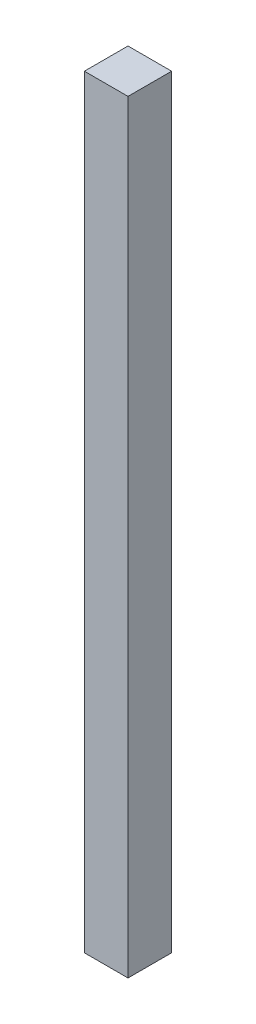
SolidWorks part; units mm, degrees
ref_plane "前视基准面" through (0, 0, 0) normal (0, 0, 1) x (1, 0, 0)
ref_plane "上视基准面" through (0, 0, 0) normal (0, 1, 0) x (1, 0, 0)
ref_plane "右视基准面" through (0, 0, 0) normal (1, 0, 0) x (0, 0, -1)
other "Configuration Table"
sketch "草图1" plane through (0, 0, 0) normal (0, 1, 0) x (1, 0, 0)
  line L1 (0, 0) -> (20, 0)
  line L2 (0, 0) -> (0, -20)
  line L3 (0, -20) -> (20, -20)
  line L4 (20, 0) -> (20, -20)
  dimension "D1" = 20
  dimension "D2" = 20
extrude "凸台-拉伸1" add sketch "草图1" along normal blind 350
